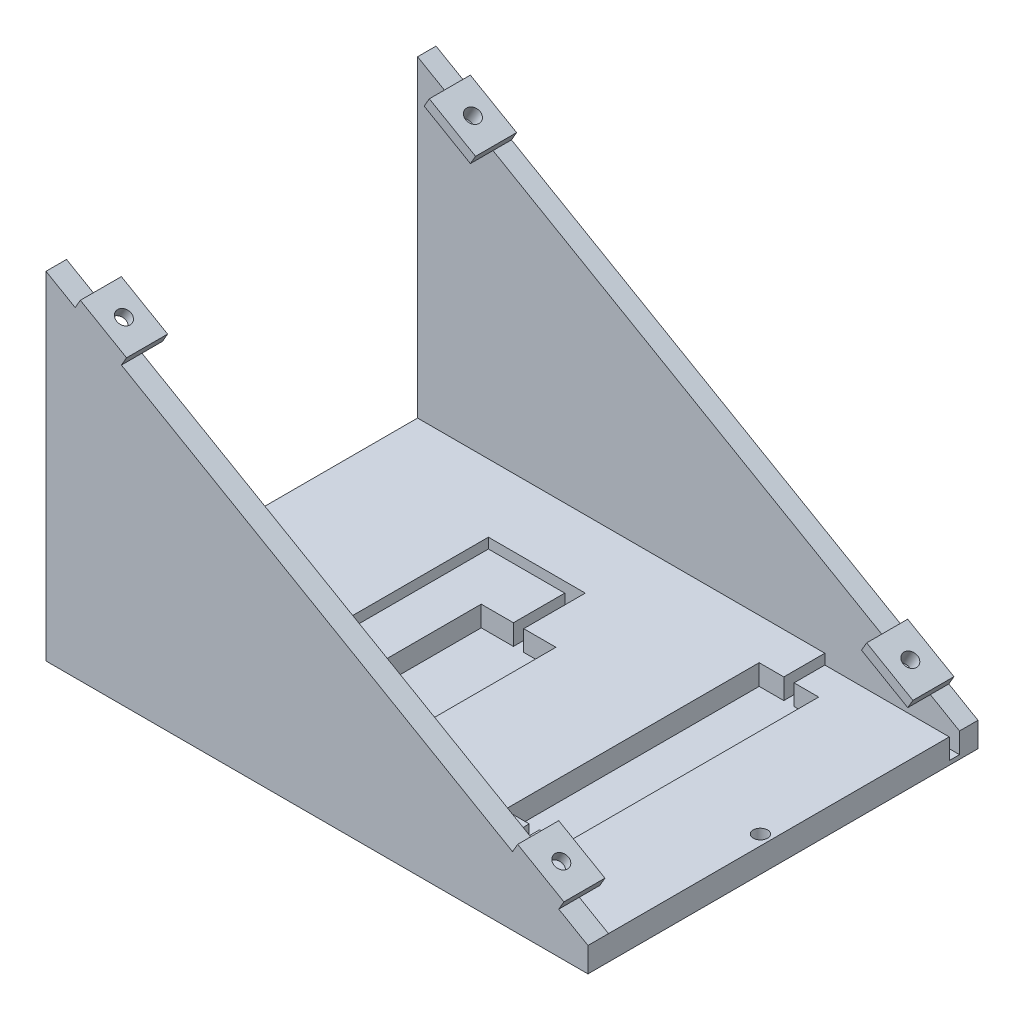
SolidWorks part; units mm, degrees
ref_plane "Front Plane" through (0, 0, 0) normal (0, 0, 1) x (1, 0, 0)
ref_plane "Top Plane" through (0, 0, 0) normal (0, 1, 0) x (1, 0, 0)
ref_plane "Right Plane" through (0, 0, 0) normal (1, 0, 0) x (0, 0, -1)
sketch "Sketch1" plane through (0, 0, 0) normal (0, 1, 0) x (1, 0, 0)
  line L1 (-66, 47.5) -> (66, 47.5)
  line L2 (-66, 47.5) -> (-66, -47.5)
  line L3 (-66, -47.5) -> (66, -47.5)
  line L4 (66, 47.5) -> (66, -47.5)
  line L5 (-66, 47.5) -> (66, -47.5) construction
  line L6 (-66, -47.5) -> (66, 47.5) construction
  point P4 (0, 0)
  dimension "D1" = 132
  dimension "D2" = 95
extrude "Boss-Extrude1" add sketch "Sketch1" along normal blind 6
sketch "Sketch3" plane through (0, 6, 0) normal (0, 1, 0) x (1, 0, 0)
  line L0 (-66, 47.5) -> (-66, -47.5) construction
  line L1 (-26, -9.5) -> (-36, -9.5)
  line L2 (-26, -9.5) -> (-26, -29.5)
  line L3 (-26, -29.5) -> (-36, -29.5)
  line L4 (-36, -9.5) -> (-36, -29.5)
  line L5 (-31, -29.5) -> (-31, -9.5) construction
  line L6 (-26, -19.5) -> (-36, -19.5) construction
  line L7 (-66, -47.5) -> (66, -47.5) construction
  point P88 (-31, -19.5)
  dimension "D1" = 30
  dimension "D2" = 18
  dimension "D3" = 20
  dimension "D4" = 10
extrude "Cut-Extrude2" cut sketch "Sketch3" against normal blind 10
sketch "Sketch4" plane through (0, 6, 0) normal (0, 1, 0) x (1, 0, 0)
  line L0 (-11.15, 24) -> (-11.15, 11.5)
  line L1 (-0.8, 11.5) -> (-8.65, 11.5)
  line L2 (-0.8, 11.5) -> (-0.8, -29.5)
  line L4 (-19, 11.5) -> (-19, -29.5)
  line L5 (-9.9, -29.5) -> (-9.9, 11.5) construction
  line L6 (-0.8, -9) -> (-19, -9) construction
  line L7 (-26, -29.5) -> (-26, -9.5) construction
  line L13 (-0.8, -29.5) -> (-8.65, -29.5)
  line L14 (-66, -47.5) -> (66, -47.5) construction
  line L15 (-8.65, 26.5) -> (-11.15, 26.5)
  line L16 (-8.65, 26.5) -> (-8.65, 11.5)
  line L19 (-9.9, 11.5) -> (-9.9, 26.5) construction
  line L20 (-8.65, 19) -> (-11.15, 19) construction
  line L22 (-11.15, 26.5) -> (-32.25, 26.5)
  line L24 (-11.15, 24) -> (-29.75, 24)
  line L25 (-32.25, 26.5) -> (-32.25, 24)
  line L26 (-21.7, 24) -> (-21.7, 26.5) construction
  line L27 (-11.15, 25.25) -> (-32.25, 25.25) construction
  line L28 (-26, -9.5) -> (-36, -9.5) construction
  line L32 (-29.75, 24) -> (-29.75, -9.5)
  line L33 (-29.75, -9.5) -> (-32.25, -9.5)
  line L34 (-32.25, 24) -> (-32.25, -9.5)
  line L35 (-31, -9.5) -> (-31, 7.25) construction
  line L36 (-29.75, 7.25) -> (-32.25, 7.25) construction
  line L37 (-11.15, 11.5) -> (-19, 11.5)
  line L38 (33.2, -29) -> (27.2, -29)
  line L39 (41.7, 33) -> (35.7, 33)
  line L40 (41.7, 33) -> (41.7, -29)
  line L41 (41.7, -29) -> (35.7, -29)
  line L42 (27.2, 33) -> (27.2, -29)
  line L43 (34.45, -29) -> (34.45, 33) construction
  line L44 (41.7, 2) -> (27.2, 2) construction
  line L45 (66, 47.5) -> (-66, 47.5) construction
  line L47 (35.7, -29) -> (35.7, -39)
  line L48 (35.7, -39) -> (33.2, -39)
  line L50 (34.45, -39) -> (34.45, -29) construction
  line L51 (35.7, -34) -> (34.45, -34) construction
  line L52 (33.2, -36.5) -> (-8.65, -36.5)
  line L54 (33.2, -39) -> (-8.65, -39)
  line L56 (12.275, -39) -> (12.275, -36.5) construction
  line L57 (33.2, -39) -> (-8.65, -39) construction
  line L58 (-11.15, -39) -> (-8.65, -39)
  line L59 (-11.15, -39) -> (-11.15, -29.5)
  line L62 (-9.9, -29.5) -> (-9.9, -39) construction
  line L63 (-11.15, -34.25) -> (-8.65, -34.25) construction
  line L64 (-11.15, -29.5) -> (-19, -29.5)
  line L65 (-8.65, -29.5) -> (-8.65, -36.5)
  line L66 (33.2, -29) -> (33.2, -36.5)
  line L67 (66, -47.5) -> (66, 47.5) construction
  line L68 (35.7, 43) -> (33.2, 43)
  line L71 (33.2, 43) -> (33.2, 33)
  line L72 (34.45, 33) -> (34.45, 43) construction
  line L73 (35.7, 38) -> (33.2, 38) construction
  line L74 (35.7, 43) -> (66, 43)
  line L76 (35.7, 40.5) -> (66, 40.5)
  line L77 (66, 43) -> (66, 40.5)
  line L78 (50.85, 40.5) -> (50.85, 43) construction
  line L79 (35.7, 41.75) -> (66, 41.75) construction
  line L80 (35.7, 40.5) -> (35.7, 33)
  line L81 (33.2, 33) -> (27.2, 33)
  point P100 (-9.9, -34.25)
  point P112 (-31, 7.25)
  point P122 (50.85, 41.75)
  point P131 (-9.9, 19)
  point P144 (-9.9, -9)
  point P163 (34.45, 38)
  point P171 (34.45, -34)
  point P229 (12.275, -39)
  point P234 (34.45, 2)
  point P254 (-21.7, 25.25)
  dimension "D1" = 41
  dimension "D2" = 18.2
  dimension "D3" = 2.5
  dimension "D4" = 7
  dimension "D5" = 15
  dimension "D6" = 18
  dimension "D7" = 2.5
  dimension "D8" = 2.5
  dimension "D9" = 62
  dimension "D10" = 14.5
  dimension "D11" = 2.5
  dimension "D12" = 10
  dimension "D13" = 14.5
  dimension "D14" = 28
  dimension "D15" = 2.5
  dimension "D16" = 41.85
  dimension "D17" = 2.5
  dimension "D18" = 7.85
  dimension "D19" = 41.85
  dimension "D20" = 2.5
  dimension "D21" = 10
  dimension "D22" = 2.5
extrude "Cut-Extrude3" cut sketch "Sketch4" against normal blind 5
sketch "Sketch6" plane through (0, 0, -47.5) normal (0, 0, -1) x (-1, 0, 0)
  line L0 (66, 6) -> (66, 82.2102)
  line L1 (66, 82.2102) -> (-66, 6)
  line L2 (-66, 6) -> (66, 6)
  dimension "D1" = 60
extrude "Boss-Extrude2" add sketch "Sketch6" against normal up to surface (4.5 mm away) up to face at (49.6, 3.5, -43)
sketch "Sketch7" plane through (0, 0, 47.5) normal (0, 0, 1) x (1, 0, 0)
  line L0 (-66, 6) -> (-66, 82.2102)
  line L1 (-66, 6) -> (66, 6)
  line L2 (66, 6) -> (-66, 82.2102)
extrude "Boss-Extrude3" add sketch "Sketch7" against normal blind 5
sketch "Sketch9" plane through (0, 0, 0) normal (0, -1, 0) x (1, 0, 0)
  line L1 (-66, 47.5) -> (66, 47.5) construction
  line L2 (66, -47.5) -> (-66, -47.5) construction
  line L4 (0, -47.5) -> (0, 47.5) construction
  circle A0 centre (63.5, 3) radius 1.75
  circle A1 centre (-63.5, 3) radius 1.75
  dimension "D2" = 3.5
  dimension "D1" = 44.5
extrude "Cut-Extrude4" cut sketch "Sketch9" against normal blind 10
sketch "Sketch10" plane through (19.0981, 33.0788, 0) normal (0.5, 0.866, 0) x (0.866, -0.5, 0)
  line L0 (-98.2628, 43) -> (-98.2628, -42.5) construction
  line L1 (54.1577, 47.5) -> (54.1577, -47.5) construction
  line L2 (-98.2628, 47.5) -> (54.1577, 47.5) construction
  line L3 (-90.0526, 37.5) -> (-77.0526, 37.5)
  line L4 (-77.0526, 47.5) -> (-77.0526, 37.5)
  line L7 (45.9474, 47.5) -> (32.9474, 47.5)
  line L12 (-22.0526, -28.5) -> (-22.0526, 28.5) construction
  line L13 (6.3874, 0) -> (-50.4926, 0) construction
  line L14 (45.9474, 47.5) -> (45.9474, 37.5)
  line L15 (45.9474, 37.5) -> (32.9474, 37.5)
  line L16 (32.9474, 47.5) -> (32.9474, 37.5)
  line L17 (39.4474, 37.5) -> (39.4474, 47.5) construction
  line L18 (45.9474, 42.5) -> (32.9474, 42.5) construction
  line L31 (-90.0526, 47.5) -> (-77.0526, 47.5)
  line L32 (-90.0526, 47.5) -> (-90.0526, 37.5)
  line L33 (-90.0526, -47.5) -> (-90.0526, -37.5)
  line L34 (-90.0526, -47.5) -> (-77.0526, -47.5)
  line L35 (-77.0526, -47.5) -> (-77.0526, -37.5)
  line L36 (-90.0526, -37.5) -> (-77.0526, -37.5)
  line L37 (45.9474, -37.5) -> (32.9474, -37.5)
  line L38 (32.9474, -47.5) -> (32.9474, -37.5)
  line L39 (45.9474, -47.5) -> (32.9474, -47.5)
  line L40 (45.9474, -47.5) -> (45.9474, -37.5)
  point P125 (39.4474, 42.5)
  point P200 (-22.0526, 0)
  dimension "D1" = 10
  dimension "D2" = 13
  dimension "D3" = 8.2102
extrude "Boss-Extrude4" add sketch "Sketch10" along normal blind 2.5
sketch "Sketch12" plane through (20.3481, 35.2439, 0) normal (0.5, 0.866, 0) x (0.866, -0.5, 0)
  line L0 (45.9474, 42.5) -> (32.9474, 42.5) construction
  line L1 (45.9474, 37.5) -> (45.9474, 47.5) construction
  line L2 (32.9474, 47.5) -> (32.9474, 37.5) construction
  line L3 (39.4474, 47.5) -> (39.4474, 37.5) construction
  line L4 (45.9474, 47.5) -> (32.9474, 47.5) construction
  line L5 (32.9474, 37.5) -> (45.9474, 37.5) construction
  line L6 (-83.5526, 47.5) -> (-83.5526, 37.5) construction
  line L9 (-77.0526, 47.5) -> (-90.0526, 47.5) construction
  line L12 (-90.0526, 37.5) -> (-77.0526, 37.5) construction
  line L15 (-83.5526, -37.5) -> (-83.5526, -47.5) construction
  line L16 (-77.0526, -37.5) -> (-90.0526, -37.5) construction
  line L17 (-90.0526, -47.5) -> (-77.0526, -47.5) construction
  line L18 (39.4474, -47.5) -> (39.4474, -37.5) construction
  line L19 (32.9474, -47.5) -> (45.9474, -47.5) construction
  line L20 (-90.0526, 37.5) -> (-77.0526, 37.5) construction
  circle A0 centre (39.4474, 42.5) radius 1.75
  circle A1 centre (-83.5526, 42.5) radius 1.75
  circle A2 centre (-83.5526, -42.5) radius 1.75
  circle A3 centre (39.4474, -42.5) radius 1.75
  dimension "D1" = 3.5
  dimension "D2" = 3.5
  dimension "D3" = 3.5
  dimension "D4" = 3.5
  dimension "D5" = 5
  dimension "D6" = 5
  dimension "D7" = 5
extrude "Cut-Extrude6" cut sketch "Sketch12" against normal blind 4
